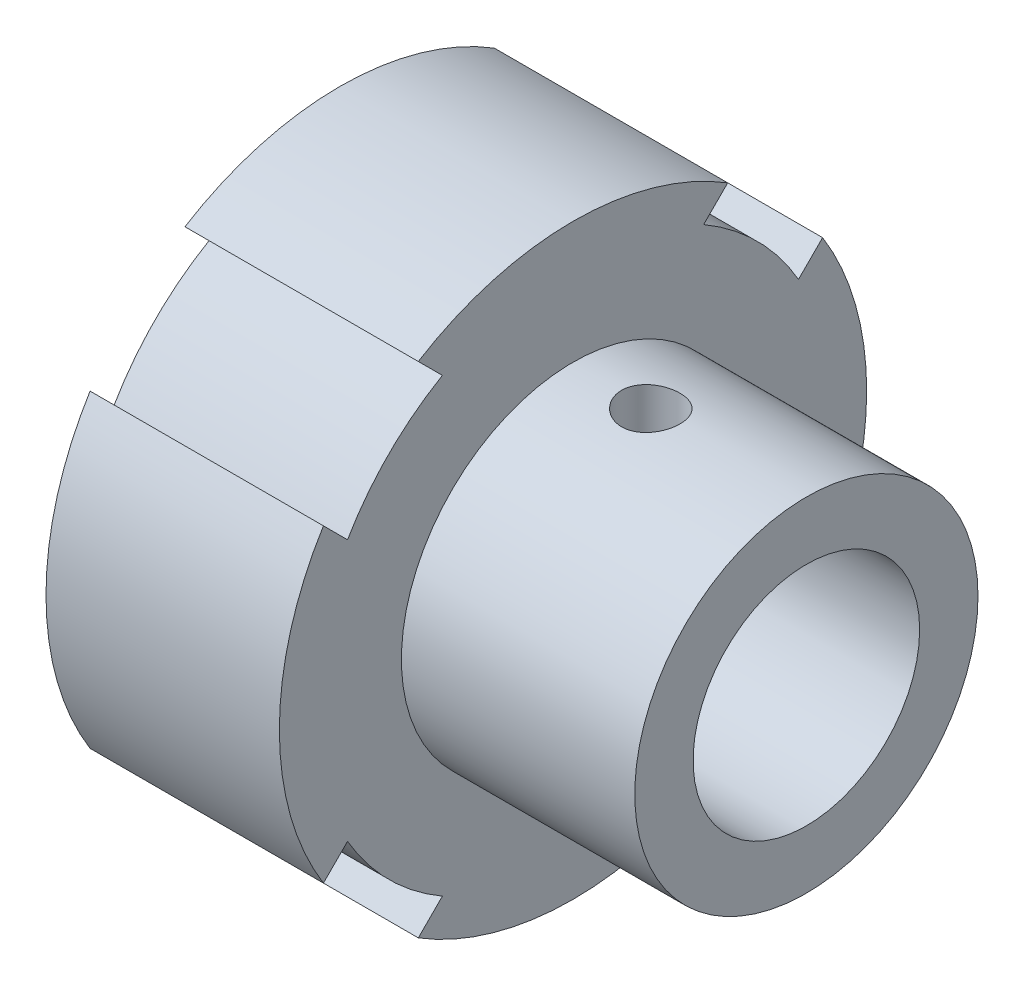
SolidWorks part; units mm, degrees
ref_plane "Front Plane" through (0, 0, 0) normal (0, 0, 1) x (1, 0, 0)
ref_plane "Top Plane" through (0, 0, 0) normal (0, 1, 0) x (1, 0, 0)
ref_plane "Right Plane" through (0, 0, 0) normal (1, 0, 0) x (0, 0, -1)
sketch "Sketch1" plane through (0, 0, 0) normal (1, 0, 0) x (0, 0, -1)
  line L0 (-11.5953, 6.7163) -> (-12.8344, 7.9554)
  line L1 (-7.9554, 12.8344) -> (-6.7163, 11.5953)
  line L2 (6.7163, 11.5953) -> (7.9554, 12.8344)
  line L3 (12.8344, 7.9554) -> (11.5953, 6.7163)
  line L4 (11.5953, -6.7163) -> (12.8344, -7.9554)
  line L5 (7.9554, -12.8344) -> (6.7163, -11.5953)
  line L6 (-6.7163, -11.5953) -> (-7.9554, -12.8344)
  line L7 (-12.8344, -7.9554) -> (-11.5953, -6.7163)
  line L8 (-11.3307, 5.0374) -> (-12.6073, 6.314)
  line L9 (-12.6073, -6.314) -> (-11.3307, -5.0374)
  line L10 (-5.0374, -11.3307) -> (-6.314, -12.6073)
  line L11 (6.314, -12.6073) -> (5.0374, -11.3307)
  line L12 (11.3307, -5.0374) -> (12.6073, -6.314)
  line L13 (12.6073, 6.314) -> (11.3307, 5.0374)
  line L14 (5.0374, 11.3307) -> (6.314, 12.6073)
  line L15 (-6.314, 12.6073) -> (-5.0374, 11.3307)
  arc A0 (-12.8344, 7.9554) -> (-12.8344, -7.9554) centre (0, 0) ccw
  arc A1 (-6.7163, 11.5953) -> (-11.5953, 6.7163) centre (0, 0) ccw
  arc A2 (7.9554, 12.8344) -> (-7.9554, 12.8344) centre (0, 0) ccw
  arc A3 (11.5953, 6.7163) -> (6.7163, 11.5953) centre (0, 0) ccw
  arc A4 (15.1, 0) -> (12.8344, 7.9554) centre (0, 0) ccw
  arc A5 (12.8344, -7.9554) -> (15.1, 0) centre (0, 0) ccw
  arc A6 (6.7163, -11.5953) -> (11.5953, -6.7163) centre (0, 0) ccw
  arc A7 (-7.9554, -12.8344) -> (7.9554, -12.8344) centre (0, 0) ccw
  arc A8 (-11.5953, -6.7163) -> (-6.7163, -11.5953) centre (0, 0) ccw
  arc A9 (-12.6073, 6.314) -> (-12.6073, -6.314) centre (0, 0) ccw
  arc A10 (-11.3307, -5.0374) -> (-5.0374, -11.3307) centre (0, 0) ccw
  arc A11 (-6.314, -12.6073) -> (6.314, -12.6073) centre (0, 0) ccw
  arc A12 (5.0374, -11.3307) -> (11.3307, -5.0374) centre (0, 0) ccw
  arc A13 (12.6073, -6.314) -> (14.1, 0) centre (0, 0) ccw
  arc A14 (14.1, 0) -> (12.6073, 6.314) centre (0, 0) ccw
  arc A15 (11.3307, 5.0374) -> (5.0374, 11.3307) centre (0, 0) ccw
  arc A16 (6.314, 12.6073) -> (-6.314, 12.6073) centre (0, 0) ccw
  arc A17 (-5.0374, 11.3307) -> (-11.3307, 5.0374) centre (0, 0) ccw
  dimension "D1" = 1
extrude "Boss-Extrude2" add sketch "Sketch1" along normal blind 10
sketch "Sketch2" plane through (10, 0, 0) normal (1, 0, 0) x (0, 0, -1)
  line L8 (-12.8344, -7.9554) -> (-11.5953, -6.7163)
  line L9 (-6.7163, -11.5953) -> (-7.9554, -12.8344)
  line L10 (7.9554, -12.8344) -> (6.7163, -11.5953)
  line L11 (11.5953, -6.7163) -> (12.8344, -7.9554)
  line L12 (12.8344, 7.9554) -> (11.5953, 6.7163)
  line L13 (6.7163, 11.5953) -> (7.9554, 12.8344)
  line L14 (-7.9554, 12.8344) -> (-6.7163, 11.5953)
  line L15 (-11.5953, 6.7163) -> (-12.8344, 7.9554)
  line L16 (-12.8344, -7.9554) -> (-11.5953, -6.7163)
  line L17 (-6.7163, -11.5953) -> (-7.9554, -12.8344)
  line L18 (7.9554, -12.8344) -> (6.7163, -11.5953)
  line L19 (11.5953, -6.7163) -> (12.8344, -7.9554)
  line L20 (12.8344, 7.9554) -> (11.5953, 6.7163)
  line L21 (6.7163, 11.5953) -> (7.9554, 12.8344)
  line L22 (-7.9554, 12.8344) -> (-6.7163, 11.5953)
  line L23 (-11.5953, 6.7163) -> (-12.8344, 7.9554)
  arc A8 (-12.8344, 7.9554) -> (-12.8344, -7.9554) centre (0, 0) ccw
  arc A9 (-11.5953, -6.7163) -> (-6.7163, -11.5953) centre (0, 0) ccw
  arc A10 (-7.9554, -12.8344) -> (7.9554, -12.8344) centre (0, 0) ccw
  arc A11 (6.7163, -11.5953) -> (11.5953, -6.7163) centre (0, 0) ccw
  arc A12 (12.8344, -7.9554) -> (12.8344, 7.9554) centre (0, 0) ccw
  arc A13 (11.5953, 6.7163) -> (6.7163, 11.5953) centre (0, 0) ccw
  arc A14 (7.9554, 12.8344) -> (-7.9554, 12.8344) centre (0, 0) ccw
  arc A15 (-6.7163, 11.5953) -> (-11.5953, 6.7163) centre (0, 0) ccw
  arc A16 (-12.8344, 7.9554) -> (-12.8344, -7.9554) centre (0, 0) ccw
  arc A17 (-11.5953, -6.7163) -> (-6.7163, -11.5953) centre (0, 0) ccw
  arc A18 (-7.9554, -12.8344) -> (7.9554, -12.8344) centre (0, 0) ccw
  arc A19 (6.7163, -11.5953) -> (11.5953, -6.7163) centre (0, 0) ccw
  arc A20 (12.8344, -7.9554) -> (12.8344, 7.9554) centre (0, 0) ccw
  arc A21 (11.5953, 6.7163) -> (6.7163, 11.5953) centre (0, 0) ccw
  arc A22 (7.9554, 12.8344) -> (-7.9554, 12.8344) centre (0, 0) ccw
  arc A23 (-6.7163, 11.5953) -> (-11.5953, 6.7163) centre (0, 0) ccw
  dimension "D1" = 0
extrude "Boss-Extrude3" add sketch "Sketch2" along normal blind 2
sketch "Sketch3" plane through (12, 0, 0) normal (1, 0, 0) x (0, 0, -1)
  circle A0 centre (0, 0) radius 5.825
  dimension "D1" = 11.65
extrude "Cut-Extrude1" cut sketch "Sketch3" against normal blind 2
sketch "Sketch4" plane through (12, 0, 0) normal (1, 0, 0) x (0, 0, -1)
  circle A0 centre (0, 0) radius 5.825 construction
  circle A1 centre (0, 0) radius 5.825
  circle A2 centre (0, 0) radius 8.825
  dimension "D1" = 3
extrude "Boss-Extrude4" add sketch "Sketch4" along normal blind 12
sketch "Sketch5" plane through (0, 0, 0) normal (0, 1, 0) x (1, 0, 0)
  circle A0 centre (16, 0) radius 1.5
  dimension "D1" = 3
extrude "Cut-Extrude2" cut sketch "Sketch5" against normal through all both and the other way through all
chamfer "Chamfer1" distance 1 angle 45 1 edges at (10, 0, -5.825)
